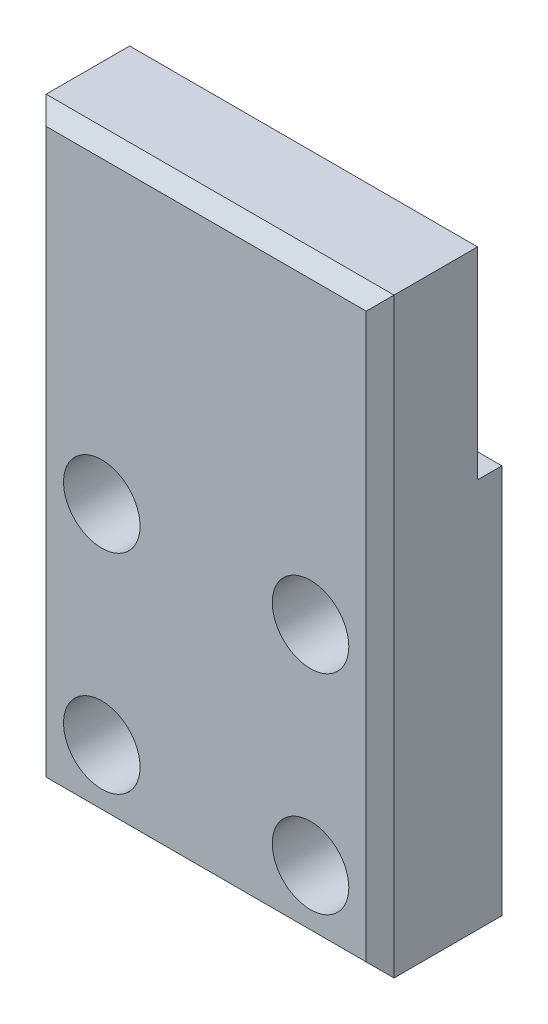
SolidWorks part; units mm, degrees
ref_plane "Front Plane" through (0, 0, 0) normal (0, 0, 1) x (1, 0, 0)
ref_plane "Top Plane" through (0, 0, 0) normal (0, 1, 0) x (1, 0, 0)
ref_plane "Right Plane" through (0, 0, 0) normal (1, 0, 0) x (0, 0, -1)
sketch "Sketch1" plane through (0, 0, 300) normal (0, 0, 1) x (1, 0, 0)
  line L0 (-135.2935, 66) -> (164.7065, 66) construction
  line L1 (75, 66) -> (125, 66)
  line L3 (85, 10) -> (115, 10)
  line L4 (85, 10) -> (75, 10)
  line L5 (75, 10) -> (75, 50)
  line L8 (75, 60) -> (75, 50)
  line L12 (115, 10) -> (125, 10)
  line L13 (125, 10) -> (125, 50)
  line L14 (125, 60) -> (125, 50)
  line L16 (75, 60) -> (75, 66)
  line L17 (125, 60) -> (125, 66)
  circle A5 centre (85, 50) radius 5.5
  circle A6 centre (85, 50) radius 5.5
  circle A8 centre (115, 50) radius 5.5
  circle A9 centre (115, 50) radius 5.5
  circle A11 centre (85, 20) radius 5.5
  circle A12 centre (85, 20) radius 5.5
  circle A15 centre (115, 20) radius 5.5
  circle A16 centre (115, 20) radius 5.5
  dimension "D1" = 2.5
  dimension "D2" = 2.5
  dimension "D3" = 2.5
  dimension "D4" = 2.5
extrude "Boss-Extrude1" add sketch "Sketch1" along normal blind 3.5
sketch "Sketch2" plane through (0, 0, 303.5) normal (0, 0, 1) x (1, 0, 0)
  line L0 (75, 10) -> (75, 85)
  line L2 (125, 85) -> (125, 10)
  line L3 (125, 10) -> (125, 66) construction
  line L4 (75, 10) -> (125, 10) construction
  line L5 (125, 10) -> (75, 10)
  line L6 (75, 85) -> (75, 95)
  line L7 (75, 95) -> (125, 95)
  line L8 (125, 95) -> (125, 85)
  circle A0 centre (85, 20) radius 5.5 construction
  circle A1 centre (115, 20) radius 5.5 construction
  circle A2 centre (115, 50) radius 5.5 construction
  circle A3 centre (85, 50) radius 5.5 construction
  circle A4 centre (85, 20) radius 5.5
  circle A5 centre (115, 20) radius 5.5
  circle A6 centre (115, 50) radius 5.5
  circle A7 centre (85, 50) radius 5.5
extrude "Boss-Extrude2" add sketch "Sketch2" along normal blind 14
chamfer "Chamfer1" distance 2 angle 45 4 edges at (100, 10, 317.5) (125, 52.5, 317.5) (100, 95, 317.5) (75, 52.5, 317.5)
